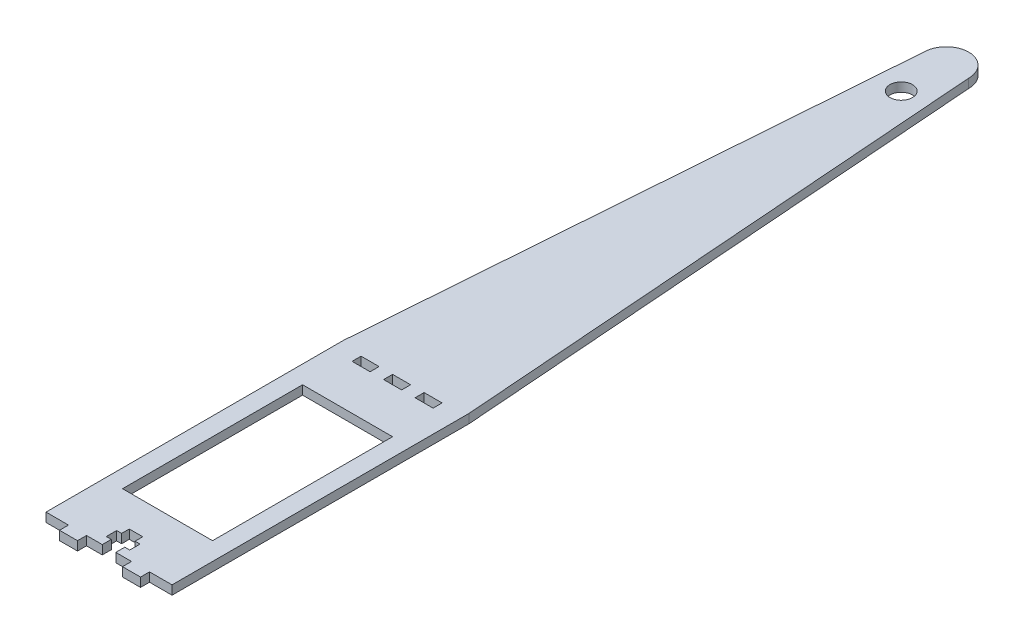
SolidWorks part; units mm, degrees
ref_plane "Front Plane" through (0, 0, 0) normal (0, 0, 1) x (1, 0, 0)
ref_plane "Top Plane" through (0, 0, 0) normal (0, 1, 0) x (1, 0, 0)
ref_plane "Right Plane" through (0, 0, 0) normal (1, 0, 0) x (0, 0, -1)
sketch "Sketch1" plane through (0, 0, 0) normal (0, 1, 0) x (1, 0, 0)
  line L0 (0, 33) -> (28, 33) construction
  line L1 (0, 0) -> (5, 0)
  line L2 (0, 0) -> (0, 66)
  line L3 (0, 66) -> (28, 66)
  line L4 (28, 0) -> (28, 66)
  line L5 (14, 66) -> (14, 0) construction
  line L6 (14, 57.25) -> (18.75, 57.25) construction
  line L7 (4, 13) -> (24, 13)
  line L8 (4, 13) -> (4, 53)
  line L9 (4, 53) -> (24, 53)
  line L10 (24, 13) -> (24, 53)
  line L11 (4, 13) -> (24, 53) construction
  line L12 (4, 53) -> (24, 13) construction
  line L13 (5, 0) -> (5, -2)
  line L19 (12.5, 6) -> (15.5, 6)
  line L20 (12.5, 6) -> (12.5, 4.3)
  line L33 (15.5, 6) -> (15.5, 4.3)
  line L34 (12.5, 6) -> (15.5, 0) construction
  line L35 (12.5, 0) -> (15.5, 6) construction
  line L36 (15.5, 2) -> (16.6, 2)
  line L38 (15.5, 4.3) -> (16.6, 4.3)
  line L39 (16.6, 2) -> (16.6, 4.3)
  line L41 (19, 0) -> (19, -2)
  line L42 (19, -2) -> (23, -2)
  line L43 (23, 0) -> (23, -2)
  line L44 (9, -2) -> (5, -2)
  line L45 (9, 0) -> (9, -2)
  line L46 (12.5, 2) -> (11.4, 2)
  line L47 (11.4, 2) -> (11.4, 4.3)
  line L48 (12.5, 4.3) -> (11.4, 4.3)
  line L49 (9, 0) -> (12.5, 0)
  line L50 (23, 0) -> (28, 0)
  line L51 (12.5, 2) -> (12.5, 0)
  line L52 (15.5, 2) -> (15.5, 0)
  line L53 (15.5, 0) -> (19, 0)
  line L54 (14, 64) -> (21, 64) construction
  line L55 (5, 65) -> (9, 65)
  line L56 (23, 63) -> (19, 63)
  line L57 (23, 63) -> (23, 65)
  line L58 (23, 65) -> (19, 65)
  line L59 (19, 63) -> (19, 65)
  line L60 (23, 63) -> (19, 65) construction
  line L61 (23, 65) -> (19, 63) construction
  line L62 (9, 63) -> (9, 65)
  line L63 (5, 63) -> (9, 63)
  line L64 (5, 63) -> (5, 65)
  line L66 (12, 63) -> (16, 63)
  line L67 (12, 63) -> (12, 65)
  line L68 (12, 65) -> (16, 65)
  line L69 (16, 63) -> (16, 65)
  line L70 (12, 63) -> (16, 65) construction
  line L71 (12, 65) -> (16, 63) construction
  point P9 (14, 33)
  point P23 (14, 3)
  point P36 (19, -1)
  dimension "D8" = 5
  dimension "D1" = 28
  dimension "D2" = 66
  dimension "D3" = 20
  dimension "D4" = 40
  dimension "D6" = 4.75
  dimension "D7" = 4.25
  dimension "D9" = 4
  dimension "D10" = 2
  dimension "D11" = 3
  dimension "D12" = 6
  dimension "D13" = 1.1
  dimension "D14" = 2.3
  dimension "D15" = 2
  dimension "D16" = 4
  dimension "D17" = 2
  dimension "D19" = 5
  dimension "D20" = 1
extrude "Boss-Extrude1" add sketch "Sketch1" along normal blind 2
sketch "Sketch2" plane through (0, 2, 0) normal (0, 1, 0) x (1, 0, 0)
  line L0 (14, 66) -> (14, 179.6943) construction
  line L1 (28, 66) -> (0, 66) construction
  line L2 (28, 66) -> (19, 186)
  line L3 (28, 66) -> (0, 66)
  line L4 (0, 66) -> (9, 186)
  arc A0 (19, 186) -> (9, 186) centre (14, 186) ccw
  circle A1 centre (14, 176) radius 2.5
  dimension "D1" = 5
  dimension "D3" = 5
  dimension "D2" = 120
  dimension "D4" = 110
extrude "Boss-Extrude2" add sketch "Sketch2" against normal blind 2
